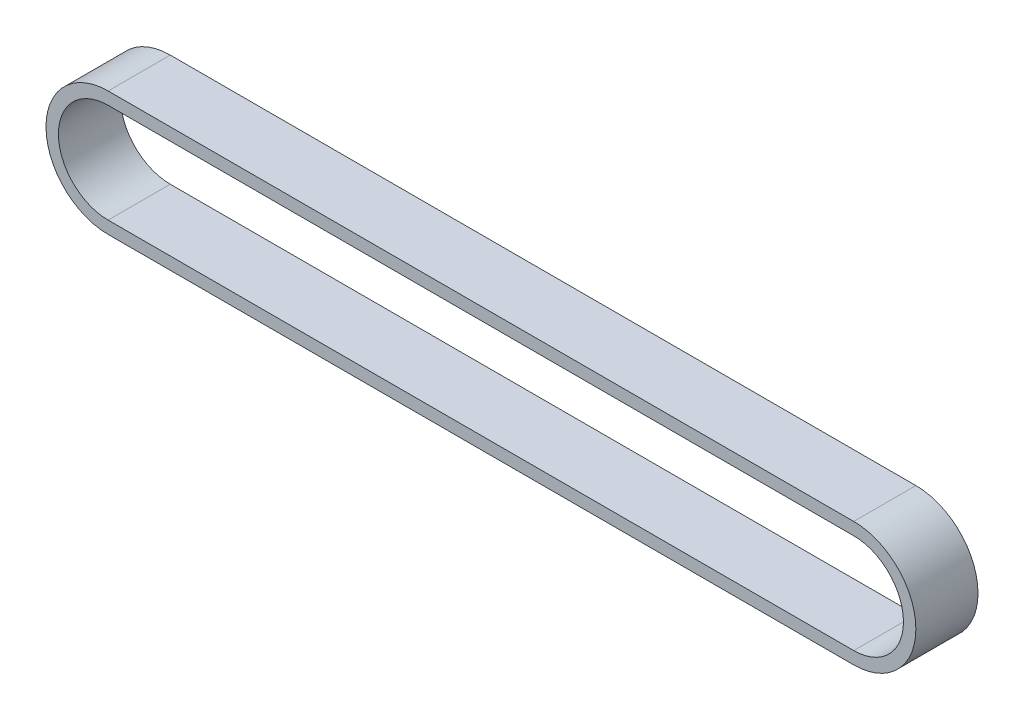
SolidWorks part; units mm, degrees
ref_plane "前视基准面" through (0, 0, 0) normal (0, 0, 1) x (1, 0, 0)
ref_plane "上视基准面" through (0, 0, 0) normal (0, 1, 0) x (1, 0, 0)
ref_plane "右视基准面" through (0, 0, 0) normal (1, 0, 0) x (0, 0, -1)
sketch "草图1" plane through (0, 0, 0) normal (0, 0, 1) x (1, 0, 0)
  line L0 (0, 0) -> (300, 0) construction
  line L1 (0, 20) -> (300, 20)
  line L2 (0, -20) -> (300, -20)
  line L3 (0, 25) -> (300, 25)
  line L4 (0, -25) -> (300, -25)
  arc A0 (0, 20) -> (0, -20) centre (0, 0) ccw
  arc A1 (300, -20) -> (300, 20) centre (300, 0) ccw
  arc A2 (300, -25) -> (300, 25) centre (300, 0) ccw
  arc A3 (0, 25) -> (0, -25) centre (0, 0) ccw
  point P3 (150, 0)
  dimension "D1" = 20
  dimension "D2" = 300
  dimension "D3" = 5
extrude "凸台-拉伸1" add sketch "草图1" along normal blind 25
